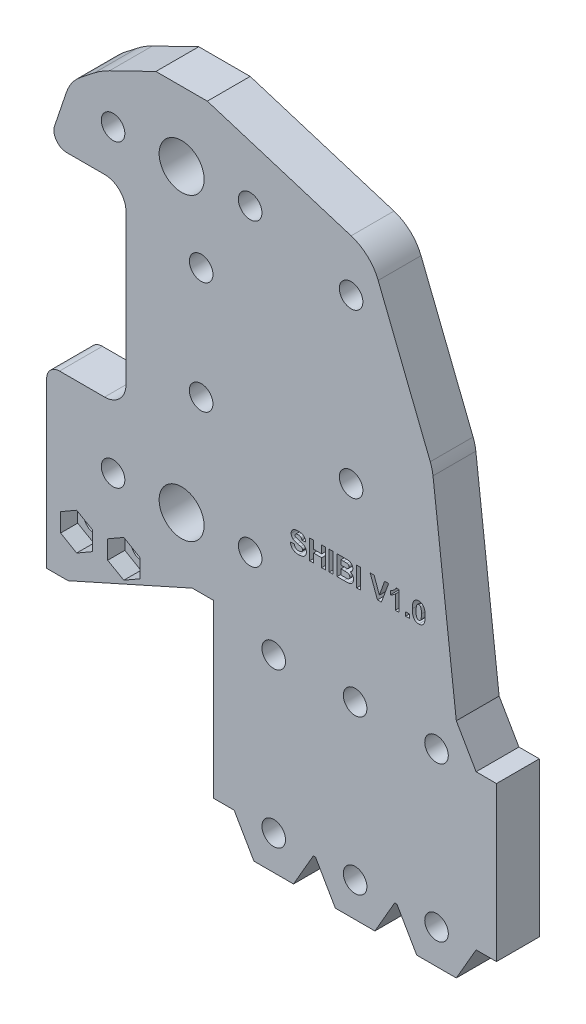
SolidWorks part; units mm, degrees
ref_plane "Спереди" through (0, 0, 0) normal (0, 0, 1) x (1, 0, 0)
ref_plane "Сверху" through (0, 0, 0) normal (0, 1, 0) x (1, 0, 0)
ref_plane "Справа" through (0, 0, 0) normal (1, 0, 0) x (0, 0, -1)
sketch "Эскиз1" plane through (0, 0, 0) normal (0, 0, 1) x (1, 0, 0)
  line L1 (-105.5196, 74.1008) -> (105.5196, 74.1008)
  line L2 (-105.5196, 74.1008) -> (-105.5196, -74.1008)
  line L3 (-105.5196, -74.1008) -> (105.5196, -74.1008)
  line L4 (105.5196, 74.1008) -> (105.5196, -74.1008)
  line L5 (-105.5196, 74.1008) -> (105.5196, -74.1008) construction
  line L6 (-105.5196, -74.1008) -> (105.5196, 74.1008) construction
  point P0 (0, 0)
extrude "Бобышка-Вытянуть1" add sketch "Эскиз1" along normal blind 10
sketch "Эскиз2" plane through (0, 0, 10) normal (0, 0, 1) x (1, 0, 0)
  line L0 (105.5196, -74.1008) -> (105.5196, -66.1008)
  line L1 (105.5196, -74.1008) -> (105.5196, 74.1008) construction
  line L2 (105.5196, -66.1008) -> (100.7596, -66.1008)
  line L3 (105.5196, -74.1008) -> (96.1396, -74.1008)
  line L4 (-105.5196, -74.1008) -> (105.5196, -74.1008) construction
  line L5 (96.1396, -74.1008) -> (100.7596, -66.1008)
  line L6 (96.1396, -74.1008) -> (86.8996, -74.1008)
  line L8 (82.2796, -66.1008) -> (86.8996, -74.1008)
  line L9 (82.2796, -66.1008) -> (81.7596, -66.1008)
  line L10 (77.1396, -74.1008) -> (81.7596, -66.1008)
  line L11 (77.1396, -74.1008) -> (67.8996, -74.1008)
  line L12 (63.2796, -66.1008) -> (67.8996, -74.1008)
  line L13 (63.2796, -66.1008) -> (62.7596, -66.1008)
  line L14 (58.1396, -74.1008) -> (62.7596, -66.1008)
  line L15 (58.1396, -74.1008) -> (48.8996, -74.1008)
  line L16 (44.2796, -66.1008) -> (48.8996, -74.1008)
  line L17 (44.2796, -66.1008) -> (39.5196, -66.1008)
  line L18 (39.5196, -66.1008) -> (39.5196, -74.1008)
  line L19 (39.5196, -74.1008) -> (48.8996, -74.1008)
  line L20 (58.1396, -74.1008) -> (67.8996, -74.1008)
  line L21 (77.1396, -74.1008) -> (86.8996, -74.1008)
  line M12 (105.5196, -74.1008) -> (105.5196, 74.1008)
  line M15 (-105.5196, -74.1008) -> (105.5196, -74.1008)
  dimension "D1" = 8
  dimension "D2" = 4.76
  dimension "D3" = 9.38
  dimension "D4" = 9.24
  dimension "D5" = 18.48
  dimension "D6" = 0.52
extrude "Вырез-Вытянуть1" cut sketch "Эскиз2" against normal through all contours L17 L18 L16 M15 | L14 L12 L13 M15 | L10 L8 L9 M15 | L5 L2 M15 M12
sketch "Эскиз3" plane through (0, 0, 10) normal (0, 0, 1) x (1, 0, 0)
  line L0 (105.5196, -66.1008) -> (105.5196, -48.1008)
  line L1 (105.5196, -66.1008) -> (105.5196, 74.1008) construction
  line L2 (105.5196, -48.1008) -> (-4.8766, -48.1008) construction
  line L3 (96.1396, -74.1008) -> (100.7596, -66.1008)
  line L4 (100.7596, -66.1008) -> (105.5196, -66.1008)
  line L5 (100.7596, -30.1008) -> (105.5196, -30.1008)
  line L6 (96.1396, -22.1008) -> (100.7596, -30.1008)
  line L7 (96.1396, -22.1008) -> (96.1396, 74.1008)
  line L8 (105.5196, 74.1008) -> (-105.5196, 74.1008) construction
  line L9 (96.1396, 74.1008) -> (105.5196, 74.1008)
  line L10 (105.5196, 74.1008) -> (105.5196, -30.1008)
  dimension "D1" = 18
extrude "Вырез-Вытянуть2" cut sketch "Эскиз3" against normal through all contours L7 L9 L10 L5 L6
sketch "Эскиз6" plane through (0, 0, 10) normal (0, 0, 1) x (1, 0, 0)
  line L0 (100.7596, -66.1008) -> (44.2796, -66.1008) construction
  line L1 (53.5196, -74.1008) -> (53.5196, -62.5603) construction
  line L2 (48.8996, -74.1008) -> (58.1396, -74.1008) construction
  line L3 (72.5196, -74.1008) -> (72.5196, -63.5637) construction
  line L4 (67.8996, -74.1008) -> (77.1396, -74.1008) construction
  line L5 (91.5196, -74.1008) -> (91.5196, -62.5603) construction
  line L6 (86.8996, -74.1008) -> (96.1396, -74.1008) construction
  circle A0 centre (72.5196, -66.1008) radius 2.5
  circle A1 centre (53.5196, -66.1008) radius 2.5
  circle A2 centre (91.5196, -66.1008) radius 2.5
  dimension "D1" = 5
extrude "Вырез-Вытянуть3" cut sketch "Эскиз6" against normal through all
sketch "Эскиз7" plane through (0, 0, 10) normal (0, 0, 1) x (1, 0, 0)
  line L0 (105.5196, -48.1008) -> (27.2781, -48.1008) construction
  line L1 (105.5196, -66.1008) -> (105.5196, -30.1008) construction
  circle A0 centre (53.5196, -66.1008) radius 2.5
  circle A1 centre (72.5196, -66.1008) radius 2.5
  circle A2 centre (91.5196, -66.1008) radius 2.5
  circle A3 centre (91.5196, -30.1008) radius 2.5
  circle A4 centre (72.5196, -30.1008) radius 2.5
  circle A5 centre (53.5196, -30.1008) radius 2.5
  dimension "D1" = 5
extrude "Вырез-Вытянуть4" cut sketch "Эскиз7" against normal through all
sketch "Эскиз8" plane through (0, 0, 0) normal (0, 0, -1) x (-1, 0, 0)
  line L0 (-105.5196, -48.1008) -> (-16.8903, -48.1008) construction
  line L1 (-105.5196, -66.1008) -> (-105.5196, -30.1008) construction
  line L2 (-105.5196, -66.1008) -> (-100.7596, -66.1008)
  line L3 (-100.7596, -66.1008) -> (-96.1396, -74.1008)
  line L4 (-96.1396, -74.1008) -> (-86.8996, -74.1008)
  line L5 (-86.8996, -74.1008) -> (-82.2796, -66.1008)
  line L6 (-82.2796, -66.1008) -> (-81.7596, -66.1008)
  line L7 (-81.7596, -66.1008) -> (-77.1396, -74.1008)
  line L8 (-77.1396, -74.1008) -> (-67.8996, -74.1008)
  line L9 (-67.8996, -74.1008) -> (-63.2796, -66.1008)
  line L10 (-63.2796, -66.1008) -> (-62.7596, -66.1008)
  line L11 (-62.7596, -66.1008) -> (-58.1396, -74.1008)
  line L12 (-58.1396, -74.1008) -> (-48.8996, -74.1008)
  line L13 (-48.8996, -74.1008) -> (-44.2796, -66.1008)
  line L14 (-44.2796, -66.1008) -> (-39.5196, -66.1008)
  line L15 (-44.2796, -30.1008) -> (-39.5196, -30.1008)
  line L16 (-48.8996, -22.1008) -> (-44.2796, -30.1008)
  line L17 (-58.1396, -22.1008) -> (-48.8996, -22.1008)
  line L18 (-62.7596, -30.1008) -> (-58.1396, -22.1008)
  line L19 (-63.2796, -30.1008) -> (-62.7596, -30.1008)
  line L20 (-67.8996, -22.1008) -> (-63.2796, -30.1008)
  line L21 (-77.1396, -22.1008) -> (-67.8996, -22.1008)
  line L22 (-81.7596, -30.1008) -> (-77.1396, -22.1008)
  line L23 (-82.2796, -30.1008) -> (-81.7596, -30.1008)
  line L24 (-86.8996, -22.1008) -> (-82.2796, -30.1008)
  line L25 (-96.1396, -22.1008) -> (-86.8996, -22.1008)
  line L26 (-100.7596, -30.1008) -> (-96.1396, -22.1008)
  line L27 (-105.5196, -30.1008) -> (-100.7596, -30.1008)
  line L29 (-53.5196, -22.1008) -> (-53.5196, -12.1008)
  circle A1 centre (-48.0196, -12.1008) radius 2.75
  circle A2 centre (-16.0196, -12.1008) radius 2.75
  dimension "D3" = 5.5
  dimension "D5" = 5.5
  dimension "D1" = 10
  dimension "D2" = 5.5
  dimension "D4" = 32
extrude "Вырез-Вытянуть5" cut sketch "Эскиз8" against normal through all contours A1 | A2
sketch "Эскиз9" plane through (0, 0, 0) normal (0, 0, -1) x (-1, 0, 0)
  line L0 (-48.0196, -12.1008) -> (-48.0196, 74.1008) construction
  line L1 (-96.1396, 74.1008) -> (105.5196, 74.1008) construction
  line L2 (-16.0196, -12.1008) -> (-16.0196, 74.1008) construction
  circle A0 centre (-48.0196, 63.8992) radius 2.75
  circle A1 centre (-16.0196, 63.8992) radius 2.75
  dimension "D2" = 5.5
  dimension "D3" = 5.5
  dimension "D1" = 76
extrude "Вырез-Вытянуть6" cut sketch "Эскиз9" against normal through all
sketch "Эскиз10" plane through (0, 0, 0) normal (0, 0, -1) x (-1, 0, 0)
  line L0 (-48.0196, 63.8992) -> (-48.0196, 57.8992)
  line L1 (-16.0196, 63.8992) -> (-16.0196, 57.8992)
  circle A0 centre (-48.0196, 57.8992) radius 2.75
  circle A1 centre (-16.0196, 57.8992) radius 2.75
  dimension "D2" = 5.5
  dimension "D1" = 6
extrude "Вырез-Вытянуть7" cut sketch "Эскиз10" against normal through all contours A0 | A1
sketch "Эскиз11" plane through (0, 0, 0) normal (0, 0, -1) x (-1, 0, 0)
  circle A0 centre (-48.0196, 63.8992) radius 2.75
  circle A1 centre (-16.0196, 63.8992) radius 2.75
  dimension "D1" = 5.5
extrude "Бобышка-Вытянуть3" add sketch "Эскиз11" against normal blind 10 contours A1 | A0
sketch "Эскиз12" plane through (0, 0, 0) normal (0, 0, -1) x (-1, 0, 0)
  line L0 (-53.5196, -74.1008) -> (-0.5196, -74.1008)
  line L1 (-48.8996, -74.1008) -> (-58.1396, -74.1008) construction
  line L2 (105.5196, -74.1008) -> (-39.5196, -74.1008) construction
  line L3 (-0.5196, -74.1008) -> (-0.5196, 74.1008)
  line L4 (-96.1396, 74.1008) -> (105.5196, 74.1008) construction
  line L5 (-0.5196, -74.1008) -> (105.5196, -74.1008)
  line L6 (105.5196, -74.1008) -> (105.5196, 74.1008)
  line L7 (105.5196, 74.1008) -> (-0.5196, 74.1008)
  line M30 (-39.5196, -74.1008) -> (105.5196, -74.1008)
  line M31 (105.5196, -74.1008) -> (105.5196, 74.1008)
  line M32 (105.5196, 74.1008) -> (-96.1396, 74.1008)
  dimension "D1" = 53
extrude "Вырез-Вытянуть8" cut sketch "Эскиз12" against normal through all contours L3 M30 M31 M32
sketch "Эскиз13" plane through (0, 0, 0) normal (0, 0, -1) x (-1, 0, 0)
  line L0 (-105.5196, -66.1008) -> (-100.7596, -66.1008)
  line L1 (-100.7596, -66.1008) -> (-96.1396, -74.1008)
  line L2 (-96.1396, -74.1008) -> (-86.8996, -74.1008)
  line L3 (-86.8996, -74.1008) -> (-82.2796, -66.1008)
  line L4 (-82.2796, -66.1008) -> (-86.8996, -74.1008) construction
  line L5 (-82.2796, -66.1008) -> (-81.7596, -66.1008)
  line L6 (-81.7596, -66.1008) -> (-77.1396, -74.1008)
  line L7 (-77.1396, -74.1008) -> (-67.8996, -74.1008)
  line L8 (-67.8996, -74.1008) -> (-63.2796, -66.1008)
  line L9 (-63.2796, -66.1008) -> (-62.7596, -66.1008)
  line L10 (-62.7596, -66.1008) -> (-58.1396, -74.1008)
  line L11 (-58.1396, -74.1008) -> (-48.8996, -74.1008)
  line L12 (-48.8996, -74.1008) -> (-44.2796, -66.1008)
  line L13 (-44.2796, -66.1008) -> (-39.5196, -66.1008)
  line L14 (-105.5196, -48.1008) -> (-24.3844, -48.1008) construction
  line L15 (-105.5196, -66.1008) -> (-105.5196, -30.1008) construction
  line L16 (-44.2796, -30.1008) -> (-39.5196, -30.1008)
  line L17 (-48.8996, -22.1008) -> (-44.2796, -30.1008)
  line L18 (-58.1396, -22.1008) -> (-48.8996, -22.1008)
  line L19 (-62.7596, -30.1008) -> (-58.1396, -22.1008)
  line L20 (-63.2796, -30.1008) -> (-62.7596, -30.1008)
  line L21 (-67.8996, -22.1008) -> (-63.2796, -30.1008)
  line L22 (-77.1396, -22.1008) -> (-67.8996, -22.1008)
  line L23 (-81.7596, -30.1008) -> (-77.1396, -22.1008)
  line L24 (-82.2796, -30.1008) -> (-81.7596, -30.1008)
  line L25 (-86.8996, -22.1008) -> (-82.2796, -30.1008)
  line L26 (-96.1396, -22.1008) -> (-86.8996, -22.1008)
  line L27 (-100.7596, -30.1008) -> (-96.1396, -22.1008)
  line L28 (-105.5196, -30.1008) -> (-100.7596, -30.1008)
  line L29 (-39.5196, -30.1008) -> (-39.5196, -66.1008)
  line L30 (-98.4496, -26.1008) -> (3.5905, -26.1008) construction
  line L31 (-39.5196, -30.1008) -> (-39.5196, -26.1008)
  line L32 (-39.5196, -30.1008) -> (-39.5196, -39.1008)
  line L33 (-39.5196, -66.1008) -> (-39.5196, -74.1008)
  line L34 (-0.5196, -74.1008) -> (-0.5196, 74.1008) construction
  line L35 (-0.5196, -39.1008) -> (-5.5196, -39.1008)
  line L36 (-39.5196, -26.1008) -> (-34.5196, -26.1008)
  line L37 (-34.5196, -26.1008) -> (-5.5196, -39.1008)
  line L38 (-39.5196, -74.1008) -> (-0.5196, -74.1008)
  line L39 (-0.5196, -74.1008) -> (-0.5196, -39.1008)
  line M13 (-0.5196, -74.1008) -> (-0.5196, 74.1008)
  line M32 (-39.5196, -66.1008) -> (-39.5196, -74.1008)
  line M33 (-39.5196, -74.1008) -> (-0.5196, -74.1008)
  dimension "D1" = 9
  dimension "D2" = 5
  dimension "D3" = 5
extrude "Вырез-Вытянуть9" cut sketch "Эскиз13" against normal through all contours L37 L36 L31 L29 L35 M32 M33 M13
sketch "Эскиз14" plane through (0, 0, 0) normal (0, 0, -1) x (-1, 0, 0)
  line L0 (-26.0196, 74.1008) -> (-0.5196, 74.1008)
  line L1 (-0.5196, 74.1008) -> (-0.5196, 57.8992)
  line L3 (-0.5196, -39.1008) -> (-0.5196, 74.1008) construction
  line L7 (-96.1396, 74.1008) -> (-0.5196, 74.1008) construction
  line L9 (-6.0558, 62.2413) -> (-11.592, 66.5835)
  line L10 (-26.0196, 74.1008) -> (-15.1867, 68.8317)
  line L11 (-0.5196, 45.7423) -> (-6.0558, 62.2413)
  line L12 (-0.5196, 45.7423) -> (-0.5196, 57.8992)
  arc A0 (-15.1867, 68.8317) -> (-11.592, 66.5835) centre (-23.9348, 50.8464) cw
  point P0 (-16.0196, -12.1008)
  point P1 (-48.0196, -12.1008)
  point P3 (-96.1396, -74.1008)
  dimension "D2" = 20
extrude "Вырез-Вытянуть11" cut sketch "Эскиз14" against normal through all
sketch "Эскиз17" plane through (0, 0, 0) normal (0, 0, -1) x (-1, 0, 0)
  line L3 (-96.1396, 74.1008) -> (-26.0196, 74.1008) construction
  line L6 (-38.0196, 74.1008) -> (-76.1396, 62.2413)
  line L7 (-96.1396, -22.1008) -> (-90.5493, 26)
  line L8 (-90.5493, 26) -> (-76.1396, 62.2413)
  line L9 (-96.1396, -22.1008) -> (-96.1396, 74.1008)
  line L10 (-96.1396, 74.1008) -> (-38.0196, 74.1008)
extrude "Вырез-Вытянуть12" cut sketch "Эскиз17" against normal blind 10
sketch "Эскиз18" plane through (0, 0, 0) normal (0, 0, -1) x (-1, 0, 0)
  line L0 (-48.0196, -12.1008) -> (-16.0196, -12.1008)
  line L1 (-48.0196, 57.8992) -> (-16.0196, 57.8992)
  circle A0 centre (-32.0196, -12.1008) radius 5
  circle A1 centre (-32.0196, 57.8992) radius 5
  point P4 (-32.0196, -12.1008)
  point P9 (-32.0196, 57.8992)
  dimension "D1" = 10
extrude "Вырез-Вытянуть13" cut sketch "Эскиз18" against normal blind 10 contours L1 A1 | L1 A1 | L0 A0 | L0 A0
fillet "Скругление1" radius 10 1 edges at (76.1396, 62.2413, 5)
fillet "Скругление2" radius 10 1 edges at (90.5493, 26, 5)
fillet "Скругление3" radius 10 1 edges at (6.0558, 62.2413, 5)
fillet "Скругление4" radius 10 1 edges at (0.5196, 45.7423, 5)
sketch "Эскиз19" plane through (0, 0, 10) normal (0, 0, 1) x (1, 0, 0)
  line L0 (1.039, 47.2905) -> (19.039, 47.2905)
  line L2 (0.5196, 2.2905) -> (19.039, 2.2905)
  line L3 (0.5196, -39.1008) -> (0.5196, 44.1093) construction
  line L5 (19.039, 47.2905) -> (19.039, 2.2905)
  line L6 (0.5196, 2.2905) -> (0, 47.2905)
  line L7 (0, 47.2905) -> (1.039, 47.2905)
  dimension "D1" = 18
  dimension "D2" = 45
extrude "Вырез-Вытянуть14" cut sketch "Эскиз19" against normal through all
fillet "Скругление5" radius 3 1 edges at (1.039, 47.2905, 5)
fillet "Скругление6" radius 5 1 edges at (19.039, 47.2905, 5)
fillet "Скругление7" radius 5 1 edges at (19.039, 2.2905, 5)
fillet "Скругление8" radius 3 1 edges at (0.5196, 2.2905, 5)
sketch "Эскиз20" plane through (0, 0, 10) normal (0, 0, 1) x (1, 0, 0)
  text T0 "<b>SHIBI V1.0</b>" font "Arial" height in points 18
extrude "Вырез-Вытянуть15" cut sketch "Эскиз20" against normal through all
sketch "Эскиз21" plane through (0, 0, 10) normal (0, 0, 1) x (1, 0, 0)
  line L0 (71.5815, 63.6594) -> (71.5815, 51.6594)
  line L1 (71.5815, 51.6594) -> (66.5815, 51.6594)
  line L2 (71.5815, 51.6594) -> (71.5815, 13.5494)
  line L3 (71.5815, 13.5494) -> (36.5815, 13.5494)
  line L4 (36.5815, 13.5494) -> (36.5815, 39.6994)
  circle A0 centre (71.5815, 51.6594) radius 2.55
  circle A1 centre (71.5815, 13.5494) radius 2.55
  circle A2 centre (36.5815, 13.5494) radius 2.55
  circle A3 centre (36.5815, 39.6994) radius 2.55
  dimension "D4" = 5.1
  dimension "D1" = 12
  dimension "D2" = 5
  dimension "D3" = 38.11
  dimension "D5" = 35
  dimension "D6" = 26.15
extrude "Вырез-Вытянуть16" cut sketch "Эскиз21" against normal through all
sketch "Эскиз22" plane through (0, 0, 0) normal (0, 0, -1) x (-1, 0, 0)
  line L1 (-66.9627, 51.6594) -> (-69.2721, 55.6594)
  line L2 (-69.2721, 55.6594) -> (-73.8909, 55.6594)
  line L3 (-73.8909, 55.6594) -> (-76.2003, 51.6594)
  line L4 (-76.2003, 51.6594) -> (-73.8909, 47.6594)
  line L5 (-73.8909, 47.6594) -> (-69.2721, 47.6594)
  line L6 (-69.2721, 47.6594) -> (-66.9627, 51.6594)
  line L7 (-66.9627, 13.5494) -> (-69.2721, 17.5494)
  line L8 (-69.2721, 17.5494) -> (-73.8909, 17.5494)
  line L9 (-73.8909, 17.5494) -> (-76.2003, 13.5494)
  line L10 (-76.2003, 13.5494) -> (-73.8909, 9.5494)
  line L11 (-73.8909, 9.5494) -> (-69.2721, 9.5494)
  line L12 (-69.2721, 9.5494) -> (-66.9627, 13.5494)
  line L13 (-31.9627, 13.5494) -> (-34.2721, 17.5494)
  line L14 (-34.2721, 17.5494) -> (-38.8909, 17.5494)
  line L15 (-38.8909, 17.5494) -> (-41.2003, 13.5494)
  line L16 (-41.2003, 13.5494) -> (-38.8909, 9.5494)
  line L17 (-38.8909, 9.5494) -> (-34.2721, 9.5494)
  line L18 (-34.2721, 9.5494) -> (-31.9627, 13.5494)
  line L19 (-31.9627, 39.6994) -> (-34.2721, 43.6994)
  line L20 (-34.2721, 43.6994) -> (-38.8909, 43.6994)
  line L21 (-38.8909, 43.6994) -> (-41.2003, 39.6994)
  line L22 (-41.2003, 39.6994) -> (-38.8909, 35.6994)
  line L23 (-38.8909, 35.6994) -> (-34.2721, 35.6994)
  line L24 (-34.2721, 35.6994) -> (-31.9627, 39.6994)
  line L25 (-43.4008, 57.8992) -> (-45.7102, 61.8992)
  line L26 (-45.7102, 61.8992) -> (-50.329, 61.8992)
  line L27 (-50.329, 61.8992) -> (-52.6384, 57.8992)
  line L28 (-52.6384, 57.8992) -> (-50.329, 53.8992)
  line L29 (-50.329, 53.8992) -> (-45.7102, 53.8992)
  line L30 (-45.7102, 53.8992) -> (-43.4008, 57.8992)
  line L31 (-11.4008, 57.8992) -> (-13.7102, 61.8992)
  line L32 (-13.7102, 61.8992) -> (-18.329, 61.8992)
  line L33 (-18.329, 61.8992) -> (-20.6384, 57.8992)
  line L34 (-20.6384, 57.8992) -> (-18.329, 53.8992)
  line L35 (-18.329, 53.8992) -> (-13.7102, 53.8992)
  line L36 (-13.7102, 53.8992) -> (-11.4008, 57.8992)
  line L37 (-43.4008, -12.1008) -> (-45.7102, -8.1008)
  line L38 (-45.7102, -8.1008) -> (-50.329, -8.1008)
  line L39 (-50.329, -8.1008) -> (-52.6384, -12.1008)
  line L40 (-52.6384, -12.1008) -> (-50.329, -16.1008)
  line L41 (-50.329, -16.1008) -> (-45.7102, -16.1008)
  line L42 (-45.7102, -16.1008) -> (-43.4008, -12.1008)
  line L43 (-11.4008, -12.1008) -> (-13.7102, -8.1008)
  line L44 (-13.7102, -8.1008) -> (-18.329, -8.1008)
  line L45 (-18.329, -8.1008) -> (-20.6384, -12.1008)
  line L46 (-20.6384, -12.1008) -> (-18.329, -16.1008)
  line L47 (-18.329, -16.1008) -> (-13.7102, -16.1008)
  line L48 (-13.7102, -16.1008) -> (-11.4008, -12.1008)
  circle A0 centre (-71.5815, 51.6594) radius 4 construction
  circle A1 centre (-71.5815, 13.5494) radius 4 construction
  circle A2 centre (-36.5815, 13.5494) radius 4 construction
  circle A3 centre (-36.5815, 39.6994) radius 4 construction
  circle A4 centre (-48.0196, 57.8992) radius 4 construction
  circle A5 centre (-16.0196, 57.8992) radius 4 construction
  circle A6 centre (-48.0196, -12.1008) radius 4 construction
  circle A7 centre (-16.0196, -12.1008) radius 4 construction
  dimension "D1" = 8
  dimension "D2" = 8
  dimension "D3" = 8
  dimension "D4" = 8
  dimension "D5" = 8
  dimension "D6" = 8
  dimension "D7" = 8
  dimension "D8" = 8
extrude "Вырез-Вытянуть17" cut sketch "Эскиз22" against normal blind 4
sketch "Эскиз23" plane through (0, 0, 0) normal (0, 0, -1) x (-1, 0, 0)
  circle A0 centre (-91.5196, -30.1008) radius 4.5
  circle A1 centre (-72.5196, -30.1008) radius 4.5
  circle A2 centre (-53.5196, -30.1008) radius 4.5
  circle A3 centre (-53.5196, -66.1008) radius 4.5
  circle A4 centre (-72.5196, -66.1008) radius 4.5
  circle A5 centre (-91.5196, -66.1008) radius 4.5
  dimension "D1" = 9
extrude "Вырез-Вытянуть18" cut sketch "Эскиз23" against normal blind 3
fillet "Скругление9" radius 1 6 edges at (87.0196, -30.1008, 0) (68.0196, -30.1008, 0) (49.0196, -30.1008, 0) (49.0196, -66.1008, 0) (68.0196, -66.1008, 0) (87.0196, -66.1008, 0)
sketch "Эскиз24" plane through (0, 0, 10) normal (0, 0, 1) x (1, 0, 0)
  line L0 (0.5196, -39.1008) -> (7.5196, -39.1008)
  line L1 (7.5196, -39.1008) -> (7.5196, -28.1708)
  line L2 (7.5196, -28.1708) -> (18.5196, -28.1708)
  circle A0 centre (18.5196, -28.1708) radius 2
  circle A1 centre (7.5196, -28.1708) radius 2
  dimension "D4" = 4
  dimension "D5" = 4
  dimension "D1" = 10.93
  dimension "D2" = 7
  dimension "D3" = 11
extrude "Вырез-Вытянуть19" cut sketch "Эскиз24" against normal through all
sketch "Эскиз25" plane through (0, 0, 10) normal (0, 0, 1) x (1, 0, 0)
  line L0 (0.5196, -39.1008) -> (0.5196, -0.7095) construction
  line L1 (22.0196, -30.1915) -> (22.0196, -26.1501)
  line L2 (22.0196, -26.1501) -> (18.5196, -24.1294)
  line L3 (18.5196, -24.1294) -> (15.0196, -26.1501)
  line L4 (15.0196, -26.1501) -> (15.0196, -30.1915)
  line L5 (15.0196, -30.1915) -> (18.5196, -32.2123)
  line L6 (18.5196, -32.2123) -> (22.0196, -30.1915)
  line L8 (7.5196, -32.2123) -> (11.0196, -30.1915)
  line L9 (11.0196, -30.1915) -> (11.0196, -26.1501)
  line L10 (11.0196, -26.1501) -> (7.5196, -24.1294)
  line L11 (7.5196, -24.1294) -> (4.0196, -26.1501)
  line L12 (4.0196, -26.1501) -> (4.0196, -30.1915)
  line L13 (4.0196, -30.1915) -> (7.5196, -32.2123)
  circle A0 centre (18.5196, -28.1708) radius 3.5 construction
  circle A1 centre (7.5196, -28.1708) radius 3.5 construction
  dimension "D1" = 7
  dimension "D2" = 7
extrude "Вырез-Вытянуть20" cut sketch "Эскиз25" against normal blind 3.3
sketch "Эскиз26" plane through (0, 0, 0) normal (0, 0, -1) x (-1, 0, 0)
  circle A0 centre (-32.0196, 57.8992) radius 5.25
  circle A1 centre (-48.0196, 57.8992) radius 2.75
  circle A2 centre (-36.5815, 39.6994) radius 2.75
  circle A3 centre (-16.0196, 57.8992) radius 2.75
  circle A4 centre (-71.5815, 51.6594) radius 2.75
  circle A5 centre (-36.5815, 13.5494) radius 2.75
  circle A6 centre (-71.5815, 13.5494) radius 2.75
  circle A7 centre (-48.0196, -12.1008) radius 2.7
  circle A8 centre (-32.0196, -12.1008) radius 5.25
  circle A9 centre (-16.0196, -12.1008) radius 2.7
  circle A10 centre (-7.5196, -28.1708) radius 2.25
  circle A11 centre (-18.5196, -28.1708) radius 2.25
  circle A12 centre (-53.5196, -30.1008) radius 2.75
  circle A13 centre (-72.5196, -30.1008) radius 2.75
  circle A14 centre (-91.5196, -30.1008) radius 2.75
  circle A15 centre (-53.5196, -66.1008) radius 2.75
  circle A16 centre (-72.5196, -66.1008) radius 2.75
  circle A17 centre (-91.5196, -66.1008) radius 2.75
  dimension "D1" = 5.5
  dimension "D2" = 5.5
  dimension "D3" = 4.5
  dimension "D4" = 5.4
  dimension "D5" = 10.5
  dimension "D6" = 10.5
extrude "Вырез-Вытянуть21" cut sketch "Эскиз26" against normal through all
sketch "Эскиз27" plane through (0, 0, 0) normal (0, 0, -1) x (-1, 0, 0)
  line L1 (-13.5947, 53.6992) -> (-11.1698, 57.8992)
  line L2 (-11.1698, 57.8992) -> (-13.5947, 62.0992)
  line L3 (-13.5947, 62.0992) -> (-18.4444, 62.0992)
  line L4 (-18.4444, 62.0992) -> (-20.8693, 57.8992)
  line L5 (-20.8693, 57.8992) -> (-18.4444, 53.6992)
  line L6 (-18.4444, 53.6992) -> (-13.5947, 53.6992)
  line L7 (-34.1566, 35.4994) -> (-31.7317, 39.6994)
  line L8 (-31.7317, 39.6994) -> (-34.1566, 43.8994)
  line L9 (-34.1566, 43.8994) -> (-39.0063, 43.8994)
  line L10 (-39.0063, 43.8994) -> (-41.4312, 39.6994)
  line L11 (-41.4312, 39.6994) -> (-39.0063, 35.4994)
  line L12 (-39.0063, 35.4994) -> (-34.1566, 35.4994)
  line L13 (-45.5947, 53.6992) -> (-43.1698, 57.8992)
  line L14 (-43.1698, 57.8992) -> (-45.5947, 62.0992)
  line L15 (-45.5947, 62.0992) -> (-50.4444, 62.0992)
  line L16 (-50.4444, 62.0992) -> (-52.8693, 57.8992)
  line L17 (-52.8693, 57.8992) -> (-50.4444, 53.6992)
  line L18 (-50.4444, 53.6992) -> (-45.5947, 53.6992)
  line L19 (-69.1566, 47.4594) -> (-66.7317, 51.6594)
  line L20 (-66.7317, 51.6594) -> (-69.1566, 55.8594)
  line L21 (-69.1566, 55.8594) -> (-74.0063, 55.8594)
  line L22 (-74.0063, 55.8594) -> (-76.4312, 51.6594)
  line L23 (-76.4312, 51.6594) -> (-74.0063, 47.4594)
  line L24 (-74.0063, 47.4594) -> (-69.1566, 47.4594)
  line L25 (-69.1566, 9.3494) -> (-66.7317, 13.5494)
  line L26 (-66.7317, 13.5494) -> (-69.1566, 17.7494)
  line L27 (-69.1566, 17.7494) -> (-74.0063, 17.7494)
  line L28 (-74.0063, 17.7494) -> (-76.4312, 13.5494)
  line L29 (-76.4312, 13.5494) -> (-74.0063, 9.3494)
  line L30 (-74.0063, 9.3494) -> (-69.1566, 9.3494)
  line L31 (-34.1566, 9.3494) -> (-31.7317, 13.5494)
  line L32 (-31.7317, 13.5494) -> (-34.1566, 17.7494)
  line L33 (-34.1566, 17.7494) -> (-39.0063, 17.7494)
  line L34 (-39.0063, 17.7494) -> (-41.4312, 13.5494)
  line L35 (-41.4312, 13.5494) -> (-39.0063, 9.3494)
  line L36 (-39.0063, 9.3494) -> (-34.1566, 9.3494)
  line L37 (-13.5947, -16.3008) -> (-11.1698, -12.1008)
  line L38 (-11.1698, -12.1008) -> (-13.5947, -7.9008)
  line L39 (-13.5947, -7.9008) -> (-18.4444, -7.9008)
  line L40 (-18.4444, -7.9008) -> (-20.8693, -12.1008)
  line L41 (-20.8693, -12.1008) -> (-18.4444, -16.3008)
  line L42 (-18.4444, -16.3008) -> (-13.5947, -16.3008)
  line L43 (-45.5947, -16.3008) -> (-43.1698, -12.1008)
  line L44 (-43.1698, -12.1008) -> (-45.5947, -7.9008)
  line L45 (-45.5947, -7.9008) -> (-50.4444, -7.9008)
  line L46 (-50.4444, -7.9008) -> (-52.8693, -12.1008)
  line L47 (-52.8693, -12.1008) -> (-50.4444, -16.3008)
  line L48 (-50.4444, -16.3008) -> (-45.5947, -16.3008)
  circle A0 centre (-16.0196, 57.8992) radius 4.2 construction
  circle A1 centre (-36.5815, 39.6994) radius 4.2 construction
  circle A2 centre (-48.0196, 57.8992) radius 4.2 construction
  circle A3 centre (-71.5815, 51.6594) radius 4.2 construction
  circle A4 centre (-71.5815, 13.5494) radius 4.2 construction
  circle A5 centre (-36.5815, 13.5494) radius 4.2 construction
  circle A6 centre (-16.0196, -12.1008) radius 4.2 construction
  circle A7 centre (-48.0196, -12.1008) radius 4.2 construction
  dimension "D1" = 8.4
  dimension "D2" = 8.4
  dimension "D3" = 8.4
  dimension "D4" = 8.4
  dimension "D5" = 8.4
  dimension "D6" = 8.4
  dimension "D7" = 8.4
  dimension "D8" = 8.4
extrude "Вырез-Вытянуть22" cut sketch "Эскиз27" against normal blind 4.2
sketch "Эскиз28" plane through (0, 0, 10) normal (0, 0, 1) x (1, 0, 0)
  line L1 (22.2696, -30.3359) -> (22.2696, -26.0057)
  line L2 (22.2696, -26.0057) -> (18.5196, -23.8407)
  line L3 (18.5196, -23.8407) -> (14.7696, -26.0057)
  line L4 (14.7696, -26.0057) -> (14.7696, -30.3359)
  line L5 (14.7696, -30.3359) -> (18.5196, -32.5009)
  line L6 (18.5196, -32.5009) -> (22.2696, -30.3359)
  line L7 (11.2696, -30.3359) -> (11.2696, -26.0057)
  line L8 (11.2696, -26.0057) -> (7.5196, -23.8407)
  line L9 (7.5196, -23.8407) -> (3.7696, -26.0057)
  line L10 (3.7696, -26.0057) -> (3.7696, -30.3359)
  line L11 (3.7696, -30.3359) -> (7.5196, -32.5009)
  line L12 (7.5196, -32.5009) -> (11.2696, -30.3359)
  circle A0 centre (18.5196, -28.1708) radius 3.75 construction
  circle A1 centre (7.5196, -28.1708) radius 3.75 construction
  dimension "D1" = 7.5
  dimension "D2" = 7.5
extrude "Вырез-Вытянуть23" cut sketch "Эскиз28" against normal blind 4
